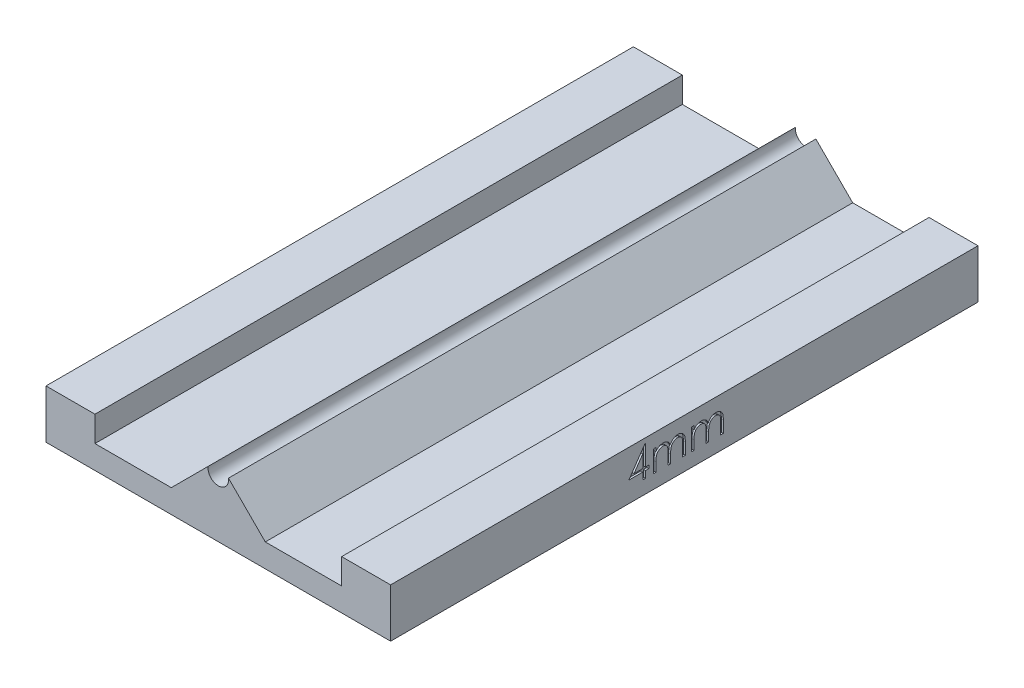
SolidWorks part; units mm, degrees
ref_plane "Front Plane" through (0, 0, 0) normal (0, 0, 1) x (1, 0, 0)
ref_plane "Top Plane" through (0, 0, 0) normal (0, 1, 0) x (1, 0, 0)
ref_plane "Right Plane" through (0, 0, 0) normal (1, 0, 0) x (0, 0, -1)
sketch "Sketch1" plane through (0, 0, 0) normal (0, 0, 1) x (1, 0, 0)
  line L0 (0, 0) -> (0, 2.9698) construction
  line L1 (0, 2.9698) -> (-10, -7.0302)
  line L2 (0, 2.9698) -> (10, -7.0302)
  line L3 (-10, -7.0302) -> (-25, -7.0302)
  line L4 (-25, -7.0302) -> (-25, 12.9698)
  line L5 (-25, 12.9698) -> (25, 12.9698)
  line L6 (25, 12.9698) -> (25, -7.0302)
  line L7 (25, -7.0302) -> (10, -7.0302)
  line L8 (-35.2, -2.0302) -> (-35.2, -12)
  line L9 (-35.2, -12) -> (35.2, -12)
  line L10 (35.2, -12) -> (35.2, -2.0302)
  line L11 (35.2, -2.0302) -> (25.2, -2.0302)
  line L12 (25.2, -2.0302) -> (25.2, -7.2302)
  line L13 (-25.2, -7.2302) -> (-9.6041, -7.2302)
  line L14 (-35.2, -2.0302) -> (-25.2, -2.0302)
  line L15 (-25.2, -2.0302) -> (-25.2, -7.2302)
  line L16 (25.2, -7.2302) -> (9.6041, -7.2302)
  line L17 (-9.6041, -7.2302) -> (-2.0792, 0.2948)
  line L18 (9.6041, -7.2302) -> (2.0792, 0.2948)
  circle A0 centre (0, 0) radius 2.1
  dimension "D12" = 4.2
  dimension "D1" = 45
  dimension "D2" = 10
  dimension "D3" = 20
  dimension "D4" = 50
  dimension "D5" = 25
  dimension "D6" = 5
  dimension "D7" = 0.2
  dimension "D8" = 0.2
  dimension "D9" = 5
  dimension "D10" = 10
  dimension "D11" = 10
  dimension "D13" = 12
  dimension "D14" = 0.2
  dimension "D15" = 0.2
extrude "Boss-Extrude1" add sketch "Sketch1" along normal blind 120 contours A0 L17 L13 L15 L14 L8 L9 L10 L11 L12 L16 L18
sketch "Sketch2" plane through (35.2, 0, 0) normal (1, 0, 0) x (0, 0, -1)
  text T0 "4mm" font "Century Gothic" height 6
extrude "Cut-Extrude1" cut sketch "Sketch2" against normal blind 0.4
